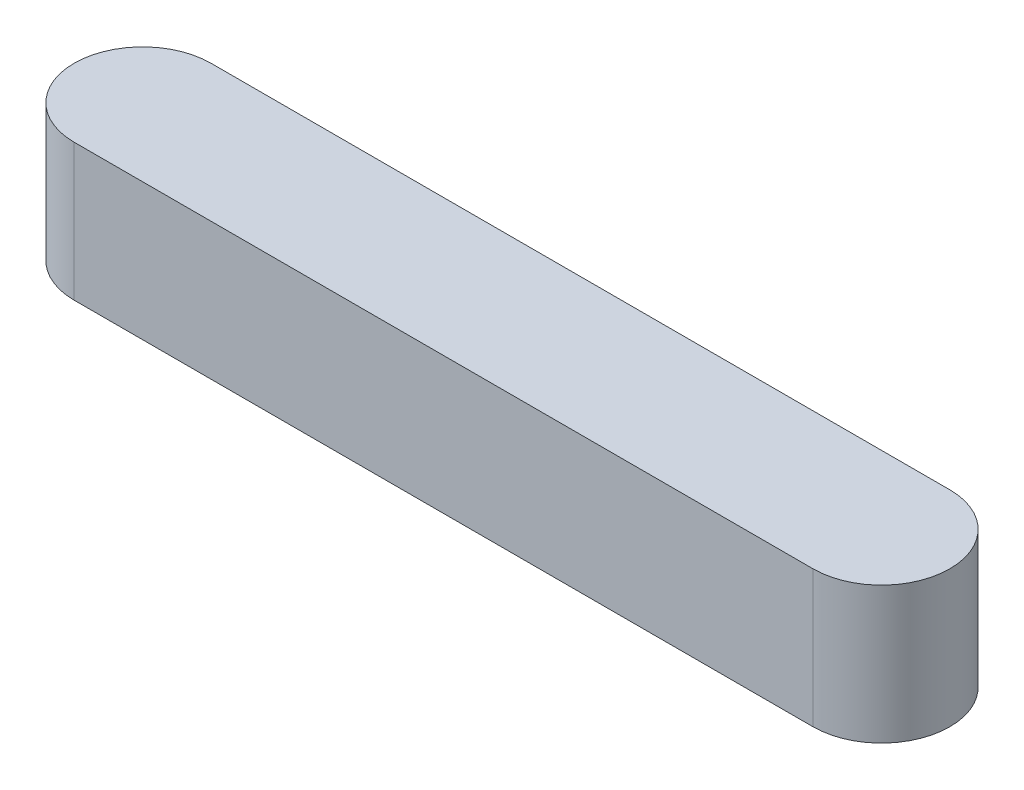
SolidWorks part; units mm, degrees
ref_plane "Спереди" through (0, 0, 0) normal (0, 0, 1) x (1, 0, 0)
ref_plane "Сверху" through (0, 0, 0) normal (0, 1, 0) x (1, 0, 0)
ref_plane "Справа" through (0, 0, 0) normal (1, 0, 0) x (0, 0, -1)
sketch "Эскиз1" plane through (0, 0, 0) normal (0, 1, 0) x (1, 0, 0)
  line L0 (0, 0) -> (27, 0) construction
  line L2 (0, 2.5) -> (27, 2.5)
  line L3 (0, -2.5) -> (27, -2.5)
  arc A0 (0, 2.5) -> (0, -2.5) centre (0, 0) ccw
  arc A1 (27, -2.5) -> (27, 2.5) centre (27, 0) ccw
  point P5 (13.5, 0)
extrude "Бобышка-Вытянуть1" add sketch "Эскиз1" along normal blind 5
